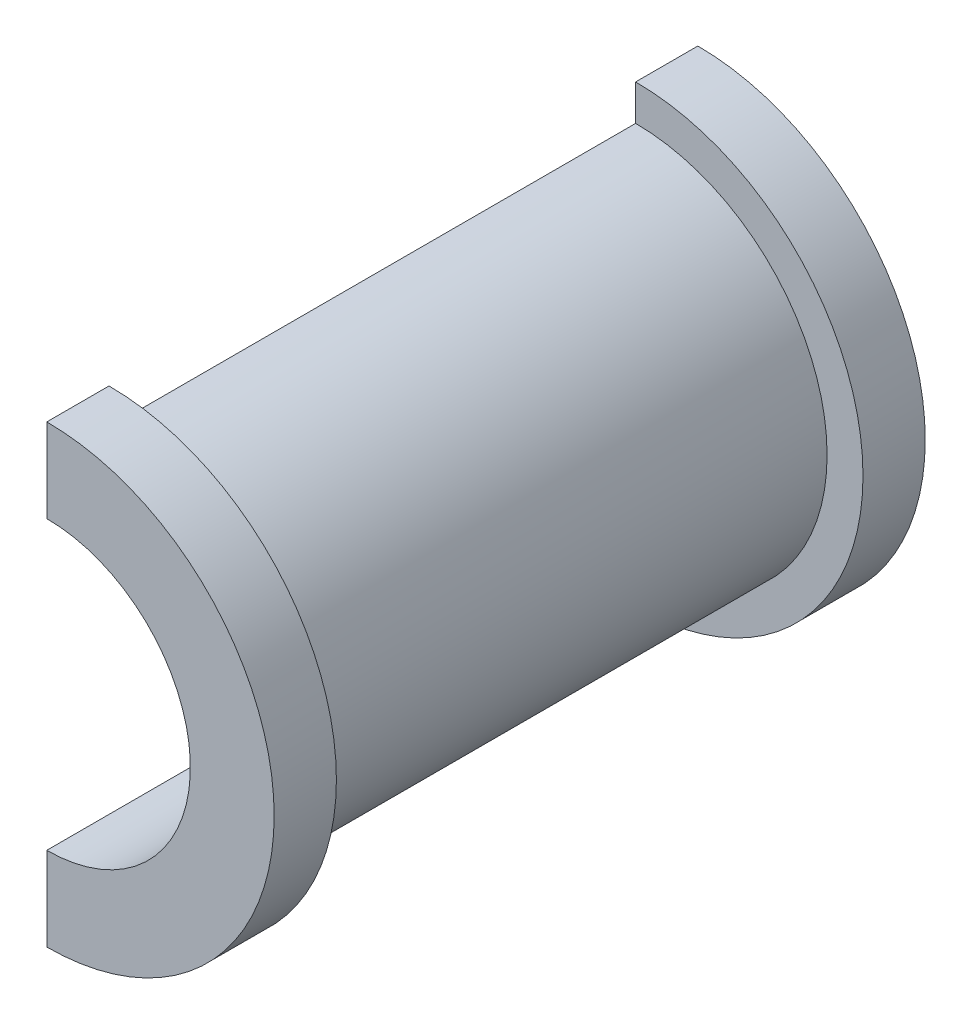
SolidWorks part; units mm, degrees
ref_plane "Front Plane" through (0, 0, 0) normal (0, 0, 1) x (1, 0, 0)
ref_plane "Top Plane" through (0, 0, 0) normal (0, 1, 0) x (1, 0, 0)
ref_plane "Right Plane" through (0, 0, 0) normal (1, 0, 0) x (0, 0, -1)
sketch "Sketch1" plane through (0, 0, 0) normal (0, 0, 1) x (1, 0, 0)
  line L0 (0, 40) -> (0, 30)
  line L1 (0, -30) -> (0, -40)
  arc A0 (0, 30) -> (0, -30) centre (0, 0) cw
  arc A1 (0, 40) -> (0, -40) centre (0, 0) cw
  dimension "D1" = 40
  dimension "D2" = 30
extrude "Boss-Extrude1" add sketch "Sketch1" along normal mid plane 110
sketch "Sketch2" plane through (0, 0, 55) normal (0, 0, 1) x (1, 0, 0)
  line L0 (0, 47.5) -> (0, 30)
  line L1 (0, -30) -> (0, -47.5)
  arc A0 (0, -30) -> (0, 30) centre (0, 0) ccw construction
  arc A1 (0, -30) -> (0, 30) centre (0, 0) ccw
  arc A2 (0, 47.5) -> (0, -47.5) centre (0, 0) cw
  dimension "D1" = 47.5
extrude "Boss-Extrude2" add sketch "Sketch2" along normal blind 13
mirror "Mirror1" about plane through (0, 0, 0) normal (0, 0, 1) of "Boss-Extrude2"
